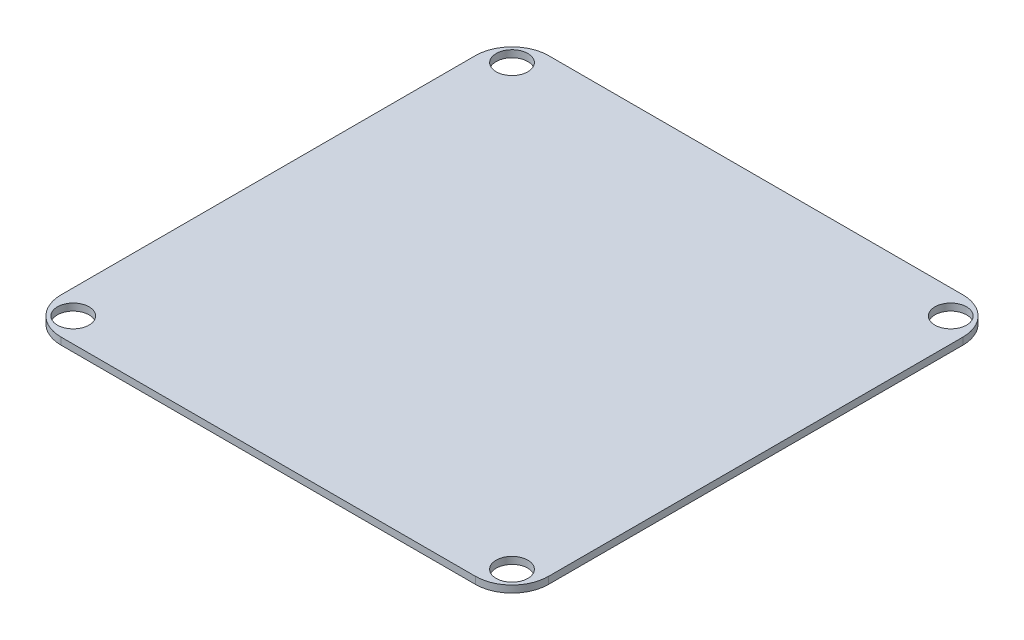
SolidWorks part; units mm, degrees
ref_plane "Front Plane" through (0, 0, 0) normal (0, 0, 1) x (1, 0, 0)
ref_plane "Top Plane" through (0, 0, 0) normal (0, 1, 0) x (1, 0, 0)
ref_plane "Right Plane" through (0, 0, 0) normal (1, 0, 0) x (0, 0, -1)
sketch "Sketch1" plane through (0, 0, 0) normal (0, 1, 0) x (1, 0, 0)
  line L1 (-21.59, 25.4) -> (21.59, 25.4)
  line L2 (-25.4, 21.59) -> (-25.4, -21.59)
  line L3 (-21.59, -25.4) -> (21.59, -25.4)
  line L4 (25.4, 21.59) -> (25.4, -21.59)
  line L5 (-25.4, 25.4) -> (25.4, -25.4) construction
  line L6 (-25.4, -25.4) -> (25.4, 25.4) construction
  circle A0 centre (-22.86, 22.86) radius 1.651
  circle A1 centre (22.86, 22.86) radius 1.651
  circle A2 centre (22.86, -22.86) radius 1.651
  circle A3 centre (-22.86, -22.86) radius 1.651
  arc A4 (-21.59, -25.4) -> (-25.4, -21.59) centre (-21.59, -21.59) cw
  arc A5 (25.4, -21.59) -> (21.59, -25.4) centre (21.59, -21.59) cw
  arc A6 (25.4, 21.59) -> (21.59, 25.4) centre (21.59, 21.59) ccw
  arc A7 (-21.59, 25.4) -> (-25.4, 21.59) centre (-21.59, 21.59) ccw
  point P0 (0, 0)
  dimension "D3" = 3.302
  dimension "D12" = 3.81
  dimension "D1" = 50.8
  dimension "D2" = 50.8
  dimension "D4" = 2.54
  dimension "D5" = 2.54
  dimension "D6" = 2.54
  dimension "D7" = 2.54
  dimension "D8" = 2.54
  dimension "D9" = 2.54
  dimension "D10" = 2.54
  dimension "D11" = 2.54
extrude "Boss-Extrude1" add sketch "Sketch1" along normal blind 0.7315
